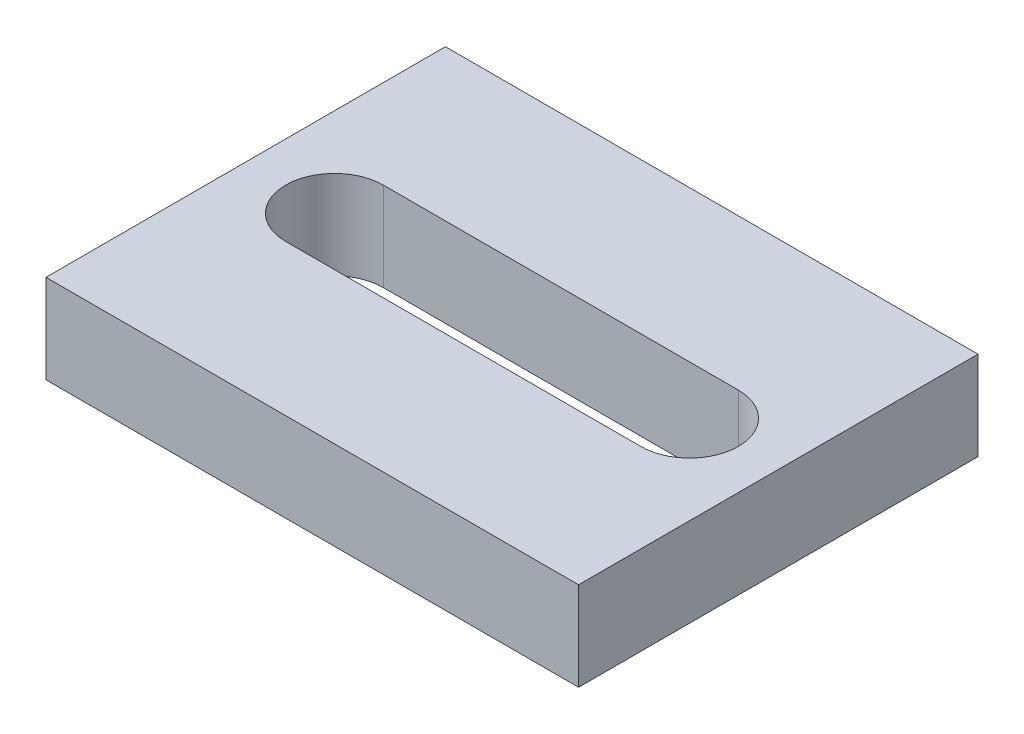
SolidWorks part; units mm, degrees
ref_plane "Front Plane" through (0, 0, 0) normal (0, 0, 1) x (1, 0, 0)
ref_plane "Top Plane" through (0, 0, 0) normal (0, 1, 0) x (1, 0, 0)
ref_plane "Right Plane" through (0, 0, 0) normal (1, 0, 0) x (0, 0, -1)
sketch "Sketch1" plane through (0, 0, 0) normal (0, 1, 0) x (1, 0, 0)
  line L0 (-25.4, 6.985) -> (25.4, 6.985)
  line L1 (38.1, 28.575) -> (-38.1, 28.575)
  line L2 (38.1, 28.575) -> (38.1, -28.575)
  line L3 (38.1, -28.575) -> (-38.1, -28.575)
  line L4 (-38.1, 28.575) -> (-38.1, -28.575)
  line L5 (0, -28.575) -> (0, 28.575) construction
  line L6 (38.1, 0) -> (-38.1, 0) construction
  line L7 (-25.4, -6.985) -> (25.4, -6.985)
  arc A0 (-25.4, 6.985) -> (-25.4, -6.985) centre (-25.4, 0) ccw
  arc A1 (25.4, -6.985) -> (25.4, 6.985) centre (25.4, 0) ccw
  point P0 (0, 0)
  dimension "D3" = 13.97
  dimension "D1" = 76.2
  dimension "D2" = 57.15
  dimension "D4" = 12.7
  dimension "D5" = 12.7
extrude "Boss-Extrude1" add sketch "Sketch1" along normal mid plane 12.7
